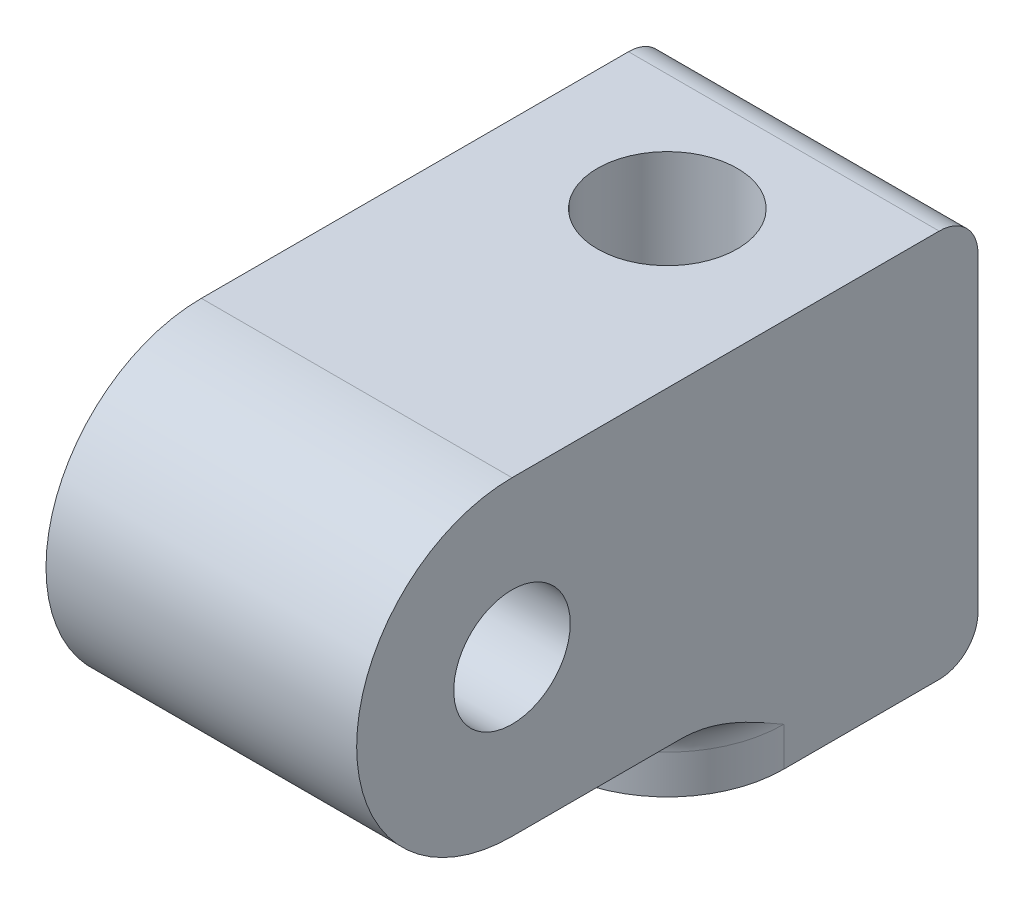
SolidWorks part; units mm, degrees
ref_plane "Front Plane" through (0, 0, 0) normal (0, 0, 1) x (1, 0, 0)
ref_plane "Top Plane" through (0, 0, 0) normal (0, 1, 0) x (1, 0, 0)
ref_plane "Right Plane" through (0, 0, 0) normal (1, 0, 0) x (0, 0, -1)
sketch "Sketch1" plane through (0, 0, 0) normal (1, 0, 0) x (0, 0, -1)
  line L1 (0, 0) -> (10.16, 0)
  line L2 (0, 0) -> (0, 2.54)
  line L3 (-5.08, 12.7) -> (10.16, 12.7)
  line L4 (10.16, 0) -> (10.16, 12.7)
  line L7 (0, 2.54) -> (-5.08, 2.54)
  circle A0 centre (-5.08, 7.62) radius 1.905
  arc A1 (-5.08, 12.7) -> (-5.08, 2.54) centre (-5.08, 7.62) ccw
  dimension "D2" = 10.16
  dimension "D3" = 3.81
  dimension "D1" = 10.16
  dimension "D4" = 5.08
  dimension "D5" = 12.7
extrude "Boss-Extrude1" add sketch "Sketch1" along normal blind 10.16
sketch "Sketch2" plane through (0, 12.7, 0) normal (0, 1, 0) x (1, 0, 0)
  line L0 (10.16, 10.16) -> (0, 10.16) construction
  circle A0 centre (5.08, 5.08) radius 2.286
  point P2 (5.08, 10.16)
  dimension "D1" = 5.08
  dimension "D2" = 4.572
extrude "Cut-Extrude1" cut sketch "Sketch2" against normal through all
fillet "Fillet2" radius 3.81 2 edges at (10.16, 1.27, 0) (0, 1.27, 0)
fillet "Fillet1" radius 1.27 5 edges at (5.08, 12.7, -10.16) (5.08, 0, -10.16) (5.08, 2.54, 0) (9.0441, 2.54, -1.1159) (1.1159, 2.54, -1.1159)
